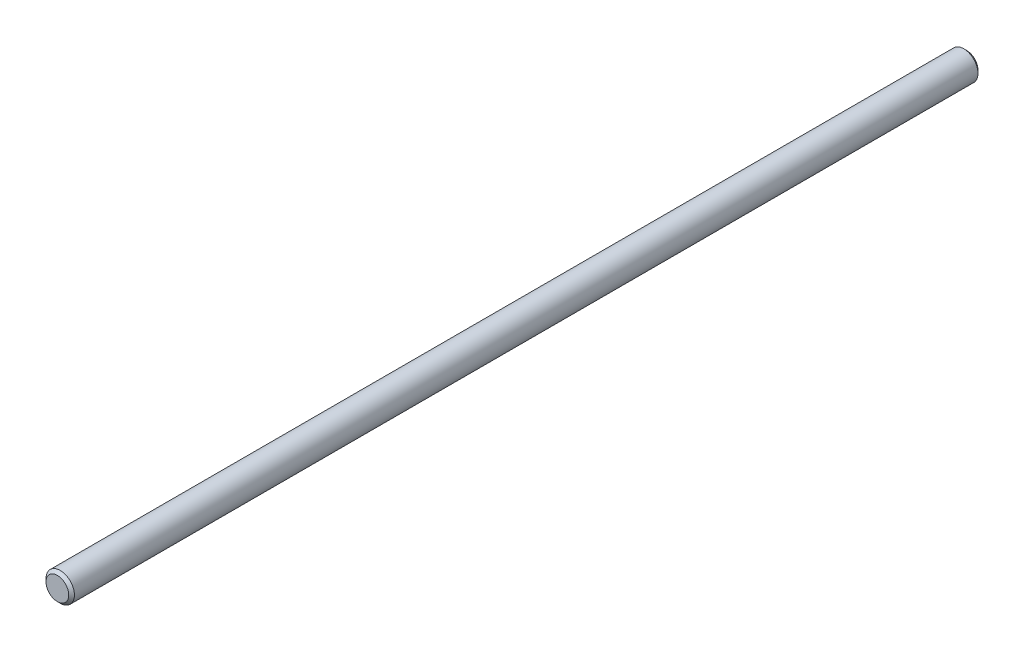
SolidWorks part; units mm, degrees
ref_plane "Front" through (0, 0, 0) normal (0, 0, 1) x (1, 0, 0)
ref_plane "Top" through (0, 0, 0) normal (0, 1, 0) x (1, 0, 0)
ref_plane "Right" through (0, 0, 0) normal (1, 0, 0) x (0, 0, -1)
sketch "Sketch1" plane through (0, 0, 0) normal (0, 0, 1) x (1, 0, 0)
  circle A0 centre (0, 0) radius 9.525
  dimension "dia" = 19.05
extrude "Extrude1" add sketch "Sketch1" along normal mid plane 609.6
sketch "Sketch2" plane through (0, 0, 0) normal (1, 0, 0) x (0, 0, -1)
  point P0 (-304.8, 9.525)
  point P1 (304.8, 9.525)
chamfer "Chamfer1" distance 1.905 angle 45 2 edges at (9.525, 0, -304.8) (9.525, 0, 304.8)
equation "\"D1@Chamfer1\" = \"dia@Sketch1\" * .1"
